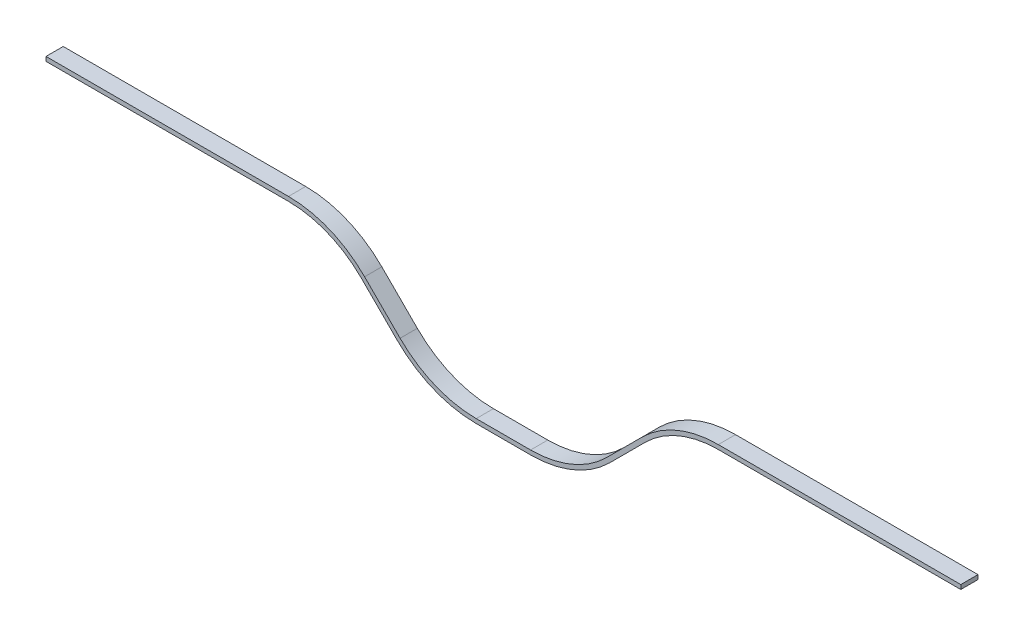
SolidWorks part; units mm, degrees
ref_plane "Alzado" through (0, 0, 0) normal (0, 0, 1) x (1, 0, 0)
ref_plane "Planta" through (0, 0, 0) normal (0, 1, 0) x (1, 0, 0)
ref_plane "Vista lateral" through (0, 0, 0) normal (1, 0, 0) x (0, 0, -1)
sketch "Croquis1" plane through (0, 0, 0) normal (0, 0, 1) x (1, 0, 0)
  line L0 (0, 0) -> (1689.3398, 0)
  line L1 (2219.6699, -219.6699) -> (2466.976, -466.976)
  line L2 (2997.306, -686.6459) -> (3375.9857, -686.6459)
  line L3 (3906.3158, -466.976) -> (4153.6218, -219.6699)
  line L4 (4683.9519, 0) -> (6373.2918, 0)
  line L5 (2000, 0) -> (4373.2918, 0) construction
  line L6 (0, -30) -> (1689.3398, -30)
  line L7 (2198.4567, -240.8831) -> (2445.7628, -488.1892)
  line L8 (2997.306, -716.6459) -> (3375.9857, -716.6459)
  line L9 (3927.529, -488.1892) -> (4174.835, -240.8831)
  line L10 (4683.9519, -30) -> (6373.2918, -30)
  line L11 (0, 0) -> (0, -30)
  line L12 (6373.2918, 0) -> (6373.2918, -30)
  arc A0 (4153.6218, -219.6699) -> (4683.9519, 0) centre (4683.9519, -750) cw
  arc A1 (3375.9857, -686.6459) -> (3906.3158, -466.976) centre (3375.9857, 63.3541) ccw
  arc A2 (2466.976, -466.976) -> (2997.306, -686.6459) centre (2997.306, 63.3541) ccw
  arc A3 (1689.3398, 0) -> (2219.6699, -219.6699) centre (1689.3398, -750) cw
  arc A4 (1689.3398, -30) -> (2198.4567, -240.8831) centre (1689.3398, -750) cw
  arc A5 (2445.7628, -488.1892) -> (2997.306, -716.6459) centre (2997.306, 63.3541) ccw
  arc A6 (3375.9857, -716.6459) -> (3927.529, -488.1892) centre (3375.9857, 63.3541) ccw
  arc A7 (4174.835, -240.8831) -> (4683.9519, -30) centre (4683.9519, -750) cw
  point P12 (3686.6459, -686.6459)
  point P15 (2686.6459, -686.6459)
  dimension "D6" = 750
  dimension "D1" = 2000
  dimension "D2" = 2000
  dimension "D3" = 135
  dimension "D4" = 135
  dimension "D5" = 1000
  dimension "D7" = 30
extrude "Saliente-Extruir1" add sketch "Croquis1" along normal blind 120
